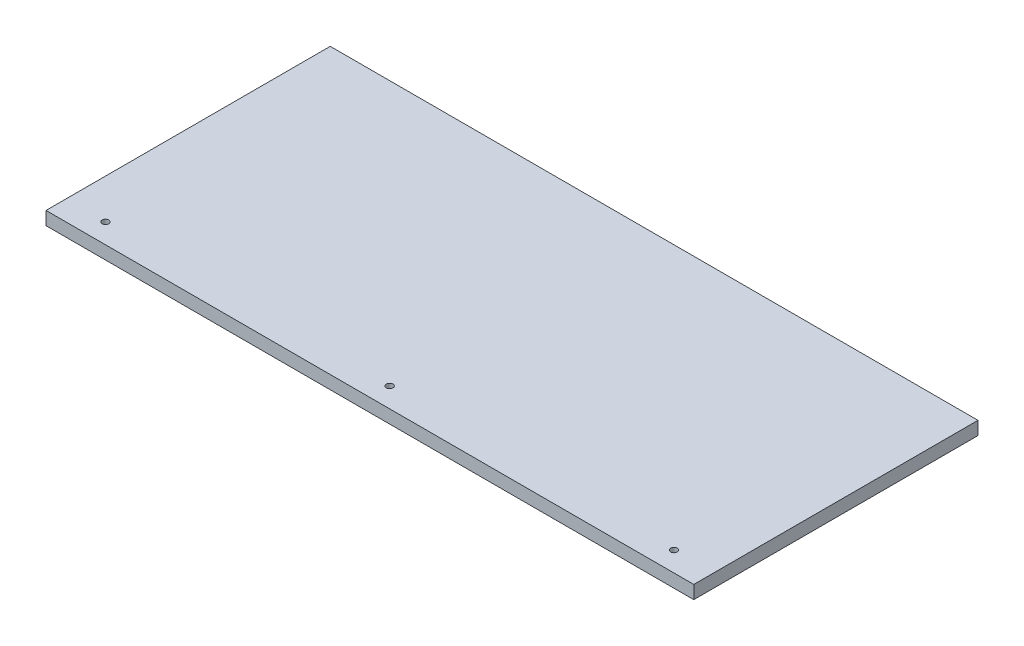
SolidWorks part; units mm, degrees
ref_plane "Plano frontal" through (0, 0, 0) normal (0, 0, 1) x (1, 0, 0)
ref_plane "Plano superior" through (0, 0, 0) normal (0, 1, 0) x (1, 0, 0)
ref_plane "Plano direito" through (0, 0, 0) normal (1, 0, 0) x (0, 0, -1)
sketch "Esboço1" plane through (0, 0, 0) normal (0, 1, 0) x (1, 0, 0)
  line L1 (0, 0) -> (490, 0)
  line L2 (0, 0) -> (0, 215)
  line L3 (0, 215) -> (490, 215)
  line L4 (490, 0) -> (490, 215)
  dimension "D1" = 215
  dimension "D2" = 490
extrude "Ressalto-extrusão1" add sketch "Esboço1" along normal blind 10
sketch "Esboço2" plane through (0, 10, 0) normal (0, 1, 0) x (1, 0, 0)
  line L0 (0, 215) -> (0, 0) construction
  line L1 (0, 0) -> (490, 0) construction
  line L2 (490, 0) -> (490, 215) construction
  circle A0 centre (30, 15) radius 2.5
  circle A1 centre (460, 15) radius 2.5
  circle A2 centre (245, 15) radius 2.5
  dimension "D3" = 5
  dimension "D4" = 5
  dimension "D7" = 5
  dimension "D1" = 30
  dimension "D2" = 15
  dimension "D5" = 15
  dimension "D6" = 30
  dimension "D8" = 15
  dimension "D9" = 245
extrude "Corte-extrusão1" cut sketch "Esboço2" against normal up to surface (10 mm away) up to face at (245, 0, -107.5)
